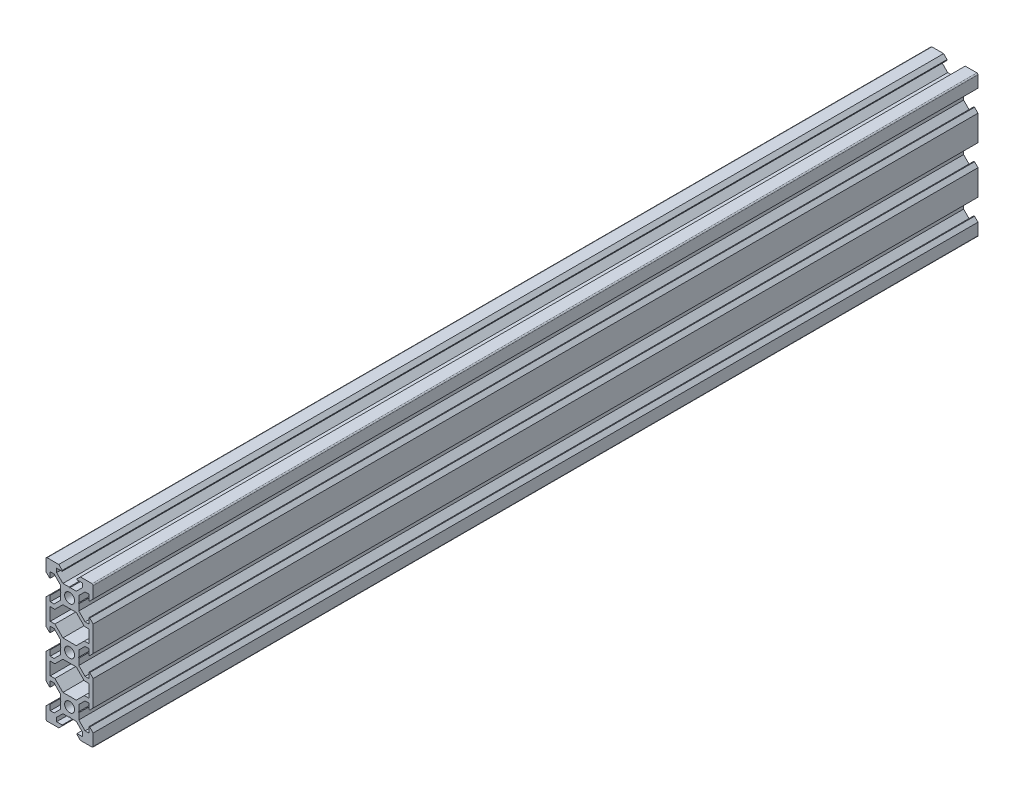
SolidWorks part; units mm, degrees
material "6061-T6 (SS)"
ref_plane "Front Plane" through (0, 0, 0) normal (0, 0, 1) x (1, 0, 0)
ref_plane "Top Plane" through (0, 0, 0) normal (0, 1, 0) x (1, 0, 0)
ref_plane "Right Plane" through (0, 0, 0) normal (1, 0, 0) x (0, 0, -1)
sketch "Sketch1" plane through (0, 0, 0) normal (0, 0, 1) x (1, 0, 0)
  line L0 (0, 0) -> (10, 0) construction
  line L1 (9.5, -30) -> (-9.5, -30)
  line L2 (10, -29.5) -> (10, 29.5)
  line L3 (9.5, 30) -> (-9.5, 30)
  line L4 (-10, -29.5) -> (-10, 29.5)
  line L5 (10, -30) -> (-10, 30) construction
  line L6 (10, 30) -> (-10, -30) construction
  circle A0 centre (0, 20) radius 2.1
  circle A1 centre (0, 0) radius 2.1
  circle A2 centre (0, -20) radius 2.1
  arc A3 (-9.5, -30) -> (-10, -29.5) centre (-9.5, -29.5) cw
  arc A4 (9.5, -30) -> (10, -29.5) centre (9.5, -29.5) ccw
  arc A5 (10, 29.5) -> (9.5, 30) centre (9.5, 29.5) ccw
  arc A6 (-9.5, 30) -> (-10, 29.5) centre (-9.5, 29.5) ccw
  point P0 (0, 0)
  line B0 (0, 20) -> (0, 30) construction
  line B1 (0, 23.69) -> (-0.21, 23.9)
  line B2 (-0.21, 23.9) -> (-2.8393, 23.9)
  line B3 (-2.8393, 23.9) -> (-5.5, 26.5607)
  line B4 (-5.5, 26.5607) -> (-5.5, 28.2)
  line B5 (-5.5, 28.2) -> (-3.125, 28.2)
  line B6 (-3.125, 28.2) -> (-3.125, 28.545)
  line B7 (-3.125, 28.545) -> (-4.58, 30)
  line B8 (-4.58, 30) -> (4.58, 30)
  line B9 (0, 20) -> (-5.9132, 25.9132) construction
  line B10 (3.125, 28.545) -> (4.58, 30)
  line B11 (3.125, 28.2) -> (3.125, 28.545)
  line B12 (5.5, 28.2) -> (3.125, 28.2)
  line B13 (5.5, 26.5607) -> (5.5, 28.2)
  line B14 (2.8393, 23.9) -> (5.5, 26.5607)
  line B15 (0.21, 23.9) -> (2.8393, 23.9)
  line B16 (0, 23.69) -> (0.21, 23.9)
  line B17 (0, 20) -> (-10, 20) construction
  line B18 (-3.69, 20) -> (-3.9, 19.79)
  line B19 (-3.9, 19.79) -> (-3.9, 17.1607)
  line B20 (-3.9, 17.1607) -> (-6.5607, 14.5)
  line B21 (-6.5607, 14.5) -> (-8.2, 14.5)
  line B22 (-8.2, 14.5) -> (-8.2, 16.875)
  line B23 (-8.2, 16.875) -> (-8.545, 16.875)
  line B24 (-8.545, 16.875) -> (-10, 15.42)
  line B25 (-10, 15.42) -> (-10, 24.58)
  line B26 (0, 20) -> (-5.9132, 14.0868) construction
  line B27 (-8.545, 23.125) -> (-10, 24.58)
  line B28 (-8.2, 23.125) -> (-8.545, 23.125)
  line B29 (-8.2, 25.5) -> (-8.2, 23.125)
  line B30 (-6.5607, 25.5) -> (-8.2, 25.5)
  line B31 (-3.9, 22.8393) -> (-6.5607, 25.5)
  line B32 (-3.9, 20.21) -> (-3.9, 22.8393)
  line B33 (-3.69, 20) -> (-3.9, 20.21)
  line B34 (0, 0) -> (-10, 0) construction
  line B35 (-3.69, 0) -> (-3.9, -0.21)
  line B36 (-3.9, -0.21) -> (-3.9, -2.8393)
  line B37 (-3.9, -2.8393) -> (-6.5607, -5.5)
  line B38 (-6.5607, -5.5) -> (-8.2, -5.5)
  line B39 (-8.2, -5.5) -> (-8.2, -3.125)
  line B40 (-8.2, -3.125) -> (-8.545, -3.125)
  line B41 (-8.545, -3.125) -> (-10, -4.58)
  line B42 (-10, -4.58) -> (-10, 4.58)
  line B43 (0, 0) -> (-5.9132, -5.9132) construction
  line B44 (-8.545, 3.125) -> (-10, 4.58)
  line B45 (-8.2, 3.125) -> (-8.545, 3.125)
  line B46 (-8.2, 5.5) -> (-8.2, 3.125)
  line B47 (-6.5607, 5.5) -> (-8.2, 5.5)
  line B48 (-3.9, 2.8393) -> (-6.5607, 5.5)
  line B49 (-3.9, 0.21) -> (-3.9, 2.8393)
  line B50 (-3.69, 0) -> (-3.9, 0.21)
  line B51 (0, -20) -> (-10, -20) construction
  line B52 (-3.69, -20) -> (-3.9, -20.21)
  line B53 (-3.9, -20.21) -> (-3.9, -22.8393)
  line B54 (-3.9, -22.8393) -> (-6.5607, -25.5)
  line B55 (-6.5607, -25.5) -> (-8.2, -25.5)
  line B56 (-8.2, -25.5) -> (-8.2, -23.125)
  line B57 (-8.2, -23.125) -> (-8.545, -23.125)
  line B58 (-8.545, -23.125) -> (-10, -24.58)
  line B59 (-10, -24.58) -> (-10, -15.42)
  line B60 (0, -20) -> (-5.9132, -25.9132) construction
  line B61 (-8.545, -16.875) -> (-10, -15.42)
  line B62 (-8.2, -16.875) -> (-8.545, -16.875)
  line B63 (-8.2, -14.5) -> (-8.2, -16.875)
  line B64 (-6.5607, -14.5) -> (-8.2, -14.5)
  line B65 (-3.9, -17.1607) -> (-6.5607, -14.5)
  line B66 (-3.9, -19.79) -> (-3.9, -17.1607)
  line B67 (-3.69, -20) -> (-3.9, -19.79)
  line B68 (0, -20) -> (0, -30) construction
  line B69 (0, -23.69) -> (0.21, -23.9)
  line B70 (0.21, -23.9) -> (2.8393, -23.9)
  line B71 (2.8393, -23.9) -> (5.5, -26.5607)
  line B72 (5.5, -26.5607) -> (5.5, -28.2)
  line B73 (5.5, -28.2) -> (3.125, -28.2)
  line B74 (3.125, -28.2) -> (3.125, -28.545)
  line B75 (3.125, -28.545) -> (4.58, -30)
  line B76 (4.58, -30) -> (-4.58, -30)
  line B77 (0, -20) -> (5.9132, -25.9132) construction
  line B78 (-3.125, -28.545) -> (-4.58, -30)
  line B79 (-3.125, -28.2) -> (-3.125, -28.545)
  line B80 (-5.5, -28.2) -> (-3.125, -28.2)
  line B81 (-5.5, -26.5607) -> (-5.5, -28.2)
  line B82 (-2.8393, -23.9) -> (-5.5, -26.5607)
  line B83 (-0.21, -23.9) -> (-2.8393, -23.9)
  line B84 (0, -23.69) -> (-0.21, -23.9)
  line B85 (0, -20) -> (10, -20) construction
  line B86 (3.69, -20) -> (3.9, -19.79)
  line B87 (3.9, -19.79) -> (3.9, -17.1607)
  line B88 (3.9, -17.1607) -> (6.5607, -14.5)
  line B89 (6.5607, -14.5) -> (8.2, -14.5)
  line B90 (8.2, -14.5) -> (8.2, -16.875)
  line B91 (8.2, -16.875) -> (8.545, -16.875)
  line B92 (8.545, -16.875) -> (10, -15.42)
  line B93 (10, -15.42) -> (10, -24.58)
  line B94 (0, -20) -> (5.9132, -14.0868) construction
  line B95 (8.545, -23.125) -> (10, -24.58)
  line B96 (8.2, -23.125) -> (8.545, -23.125)
  line B97 (8.2, -25.5) -> (8.2, -23.125)
  line B98 (6.5607, -25.5) -> (8.2, -25.5)
  line B99 (3.9, -22.8393) -> (6.5607, -25.5)
  line B100 (3.9, -20.21) -> (3.9, -22.8393)
  line B101 (3.69, -20) -> (3.9, -20.21)
  line B102 (0, 0) -> (10, 0) construction
  line B103 (3.69, 0) -> (3.9, 0.21)
  line B104 (3.9, 0.21) -> (3.9, 2.8393)
  line B105 (3.9, 2.8393) -> (6.5607, 5.5)
  line B106 (6.5607, 5.5) -> (8.2, 5.5)
  line B107 (8.2, 5.5) -> (8.2, 3.125)
  line B108 (8.2, 3.125) -> (8.545, 3.125)
  line B109 (8.545, 3.125) -> (10, 4.58)
  line B110 (10, 4.58) -> (10, -4.58)
  line B111 (0, 0) -> (5.9132, 5.9132) construction
  line B112 (8.545, -3.125) -> (10, -4.58)
  line B113 (8.2, -3.125) -> (8.545, -3.125)
  line B114 (8.2, -5.5) -> (8.2, -3.125)
  line B115 (6.5607, -5.5) -> (8.2, -5.5)
  line B116 (3.9, -2.8393) -> (6.5607, -5.5)
  line B117 (3.9, -0.21) -> (3.9, -2.8393)
  line B118 (3.69, 0) -> (3.9, -0.21)
  line B119 (0, 20) -> (10, 20) construction
  line B120 (3.69, 20) -> (3.9, 20.21)
  line B121 (3.9, 20.21) -> (3.9, 22.8393)
  line B122 (3.9, 22.8393) -> (6.5607, 25.5)
  line B123 (6.5607, 25.5) -> (8.2, 25.5)
  line B124 (8.2, 25.5) -> (8.2, 23.125)
  line B125 (8.2, 23.125) -> (8.545, 23.125)
  line B126 (8.545, 23.125) -> (10, 24.58)
  line B127 (10, 24.58) -> (10, 15.42)
  line B128 (0, 20) -> (5.9132, 25.9132) construction
  line B129 (8.545, 16.875) -> (10, 15.42)
  line B130 (8.2, 16.875) -> (8.545, 16.875)
  line B131 (8.2, 14.5) -> (8.2, 16.875)
  line B132 (6.5607, 14.5) -> (8.2, 14.5)
  line B133 (3.9, 17.1607) -> (6.5607, 14.5)
  line B134 (3.9, 19.79) -> (3.9, 17.1607)
  line B135 (3.69, 20) -> (3.9, 19.79)
  line B136 (-8.2, 7.3) -> (-8.2, 12.7)
  line B137 (-8.2, 12.7) -> (-6.2393, 12.7)
  line B138 (-6.2393, 12.7) -> (-2.8393, 16.1)
  line B139 (-2.8393, 16.1) -> (2.8393, 16.1)
  line B140 (0, 16.1) -> (0, 10) construction
  line B141 (0, 10) -> (-8.2, 10) construction
  line B142 (6.2393, 12.7) -> (2.8393, 16.1)
  line B143 (8.2, 12.7) -> (6.2393, 12.7)
  line B144 (8.2, 7.3) -> (8.2, 12.7)
  line B145 (8.2, 7.3) -> (6.2393, 7.3)
  line B146 (6.2393, 7.3) -> (2.8393, 3.9)
  line B147 (-2.8393, 3.9) -> (2.8393, 3.9)
  line B148 (-6.2393, 7.3) -> (-2.8393, 3.9)
  line B149 (-8.2, 7.3) -> (-6.2393, 7.3)
  line B150 (0, 16.1) -> (0, 20) construction
  line B151 (0, 20) -> (-5.0927, 14.9073) construction
  line B152 (-8.2, -12.7) -> (-8.2, -7.3)
  line B153 (-8.2, -7.3) -> (-6.2393, -7.3)
  line B154 (-6.2393, -7.3) -> (-2.8393, -3.9)
  line B155 (-2.8393, -3.9) -> (2.8393, -3.9)
  line B156 (0, -3.9) -> (0, -10) construction
  line B157 (0, -10) -> (-8.2, -10) construction
  line B158 (6.2393, -7.3) -> (2.8393, -3.9)
  line B159 (8.2, -7.3) -> (6.2393, -7.3)
  line B160 (8.2, -12.7) -> (8.2, -7.3)
  line B161 (8.2, -12.7) -> (6.2393, -12.7)
  line B162 (6.2393, -12.7) -> (2.8393, -16.1)
  line B163 (-2.8393, -16.1) -> (2.8393, -16.1)
  line B164 (-6.2393, -12.7) -> (-2.8393, -16.1)
  line B165 (-8.2, -12.7) -> (-6.2393, -12.7)
  line B166 (0, -3.9) -> (0, 0) construction
  line B167 (0, 0) -> (-5.0927, -5.0927) construction
  dimension "D3" = 4.2
  dimension "D5" = 0.5
  dimension "D1" = 20
  dimension "D2" = 60
  dimension "D4" = 40
sketch_block_instance "V Slot 1-4"
sketch_block "V Slot 1" parameters "D1"=10, "D2"=11, "D3"=4.3, "D4"=1.8, "D5"=0.21, "D6"=45, "D7"=9.16, "D8"=1.5, "D9"=6.25
sketch_block_instance "V Slot 1-5"
sketch_block_instance "V Slot 1-6"
sketch_block_instance "V Slot 1-7"
sketch_block_instance "V Slot 1-8"
sketch_block_instance "V Slot 1-9"
sketch_block_instance "V Slot 1-10"
sketch_block_instance "V Slot 1-11"
sketch_block_instance "Center Cutout 1-1"
sketch_block "Center Cutout 1" parameters "D1"=5.4, "D2"=12.2, "D3"=8.2, "D4"=45, "D5"=10, "D6"=1.5
sketch_block_instance "Center Cutout 1-2"
extrude "Boss-Extrude1" add sketch "Sketch1" along normal blind 375 contours B135 B120 B121 B122 B123 B124 B125 B126 L2 A5 L3 B10 B11 B12 B13 B14 B15 B16 B1 B2 B3 B4 B5 B6 B7 A6 L4 B27 B28 B29 B30 B31 B32 B33 B18 B19 B20 B21 B22 B23 B24 B44 B45 B46 B47 B48 B49 B50 B35
